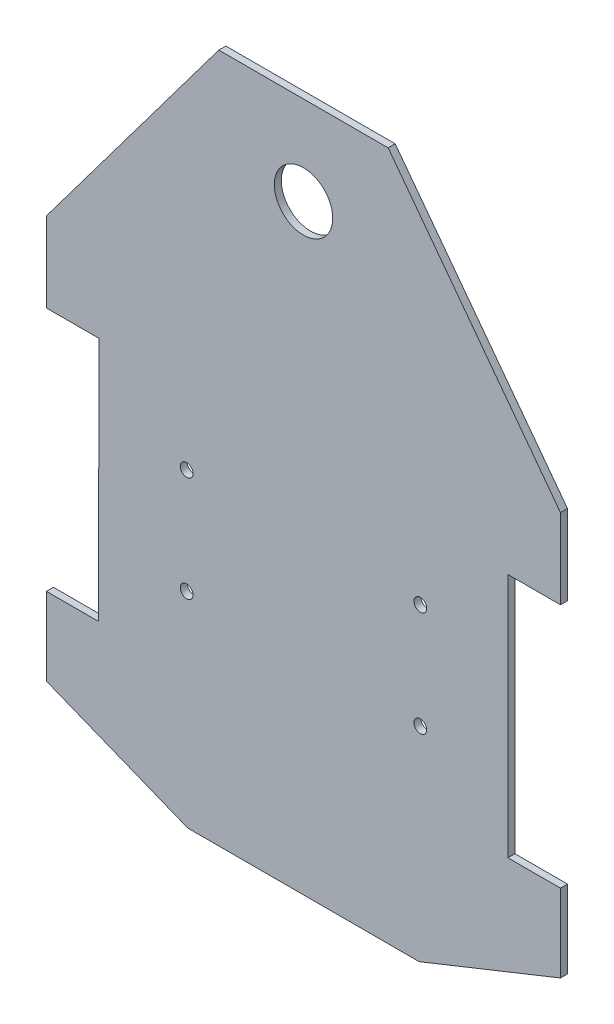
SolidWorks part; units mm, degrees
ref_plane "Front Plane" through (0, 0, 0) normal (0, 0, 1) x (1, 0, 0)
ref_plane "Top Plane" through (0, 0, 0) normal (0, 1, 0) x (1, 0, 0)
ref_plane "Right Plane" through (0, 0, 0) normal (1, 0, 0) x (0, 0, -1)
sketch "Sketch1" plane through (0, 0, 0) normal (0, 0, 1) x (1, 0, 0)
  line L0 (-19.8074, -59) -> (-44, -49.323)
  line L1 (-44, -49.323) -> (-44, -36)
  line L2 (-44, -36) -> (-35.1099, -36)
  line L3 (-35.1099, -36) -> (-35, 6)
  line L4 (-35, 6) -> (-44, 6)
  line L5 (-44, 6) -> (-44, 19.6667)
  line L6 (-44, 19.6667) -> (-14.5, 59)
  line L7 (-14.5, 59) -> (14.5, 59)
  line L8 (14.5, 59) -> (44, 19.6667)
  line L9 (44, 19.6667) -> (44, 6)
  line L10 (44, 6) -> (35, 6)
  line L11 (35, 6) -> (35, -36)
  line L12 (35, -36) -> (44, -36)
  line L13 (44, -36) -> (44, -49.323)
  line L14 (44, -49.323) -> (19.8074, -59)
  line L15 (19.8074, -59) -> (-19.8074, -59)
  circle A0 centre (-20, -6) radius 1.1
  circle A1 centre (-20, -24) radius 1.1
  circle A2 centre (20, -6) radius 1.1
  circle A3 centre (20, -24) radius 1.1
extrude "Boss-Extrude1" add sketch "Sketch1" along normal blind 1.2
sketch "Sketch2" plane through (0, 0, 1.2) normal (0, 0, 1) x (1, 0, 0)
  line L0 (0, 59) -> (0, -59) construction
  line L1 (14.5, 59) -> (-14.5, 59) construction
  line L2 (-19.8074, -59) -> (19.8074, -59) construction
  circle A0 centre (0, 43.8089) radius 5
  dimension "D1" = 10
extrude "Cut-Extrude1" cut sketch "Sketch2" against normal through all
